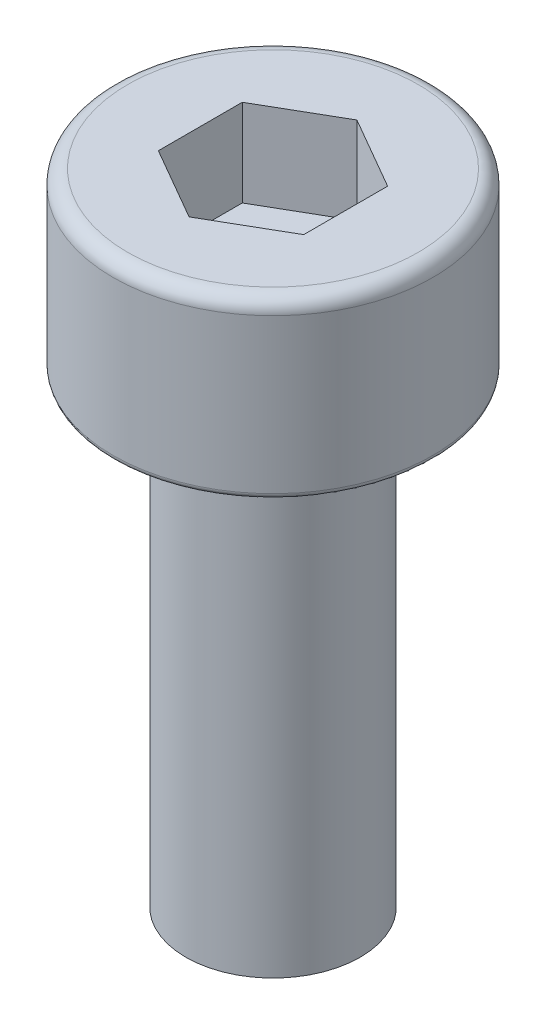
SolidWorks part; units mm, degrees
material "Liga de aço"
ref_plane "Plano frontal" through (0, 0, 0) normal (0, 0, 1) x (1, 0, 0)
ref_plane "Plano superior" through (0, 0, 0) normal (0, 1, 0) x (1, 0, 0)
ref_plane "Plano direito" through (0, 0, 0) normal (1, 0, 0) x (0, 0, -1)
sketch "Esboço1" plane through (0, 0, 0) normal (0, 1, 0) x (1, 0, 0)
  circle A0 centre (0, 0) radius 2.75
  dimension "D1" = 5.5
extrude "Ressalto-extrusão1" add sketch "Esboço1" along normal blind 3
sketch "Esboço2" plane through (0, 3, 0) normal (0, 1, 0) x (1, 0, 0)
  line L1 (0, 1.4434) -> (-1.25, 0.7217)
  line L2 (-1.25, 0.7217) -> (-1.25, -0.7217)
  line L3 (-1.25, -0.7217) -> (0, -1.4434)
  line L4 (0, -1.4434) -> (1.25, -0.7217)
  line L5 (1.25, -0.7217) -> (1.25, 0.7217)
  line L6 (1.25, 0.7217) -> (0, 1.4434)
  circle A0 centre (0, 0) radius 1.25 construction
  dimension "D1" = 2.5
extrude "Corte-extrusão1" cut sketch "Esboço2" against normal blind 1.5
fillet "Filete1" radius 0.25 1 edges at (0, 3, 2.75)
fillet "Filete2" radius 0.1 1 edges at (0, 0, 2.75)
sketch "Esboço3" plane through (0, 0, 0) normal (0, -1, 0) x (1, 0, 0)
  circle A0 centre (0, 0) radius 1.5
  dimension "D1" = 3
extrude "Ressalto-extrusão2" add sketch "Esboço3" along normal blind 8
cosmetic thread "Representação de rosca1" parameters "D2"=1.993
